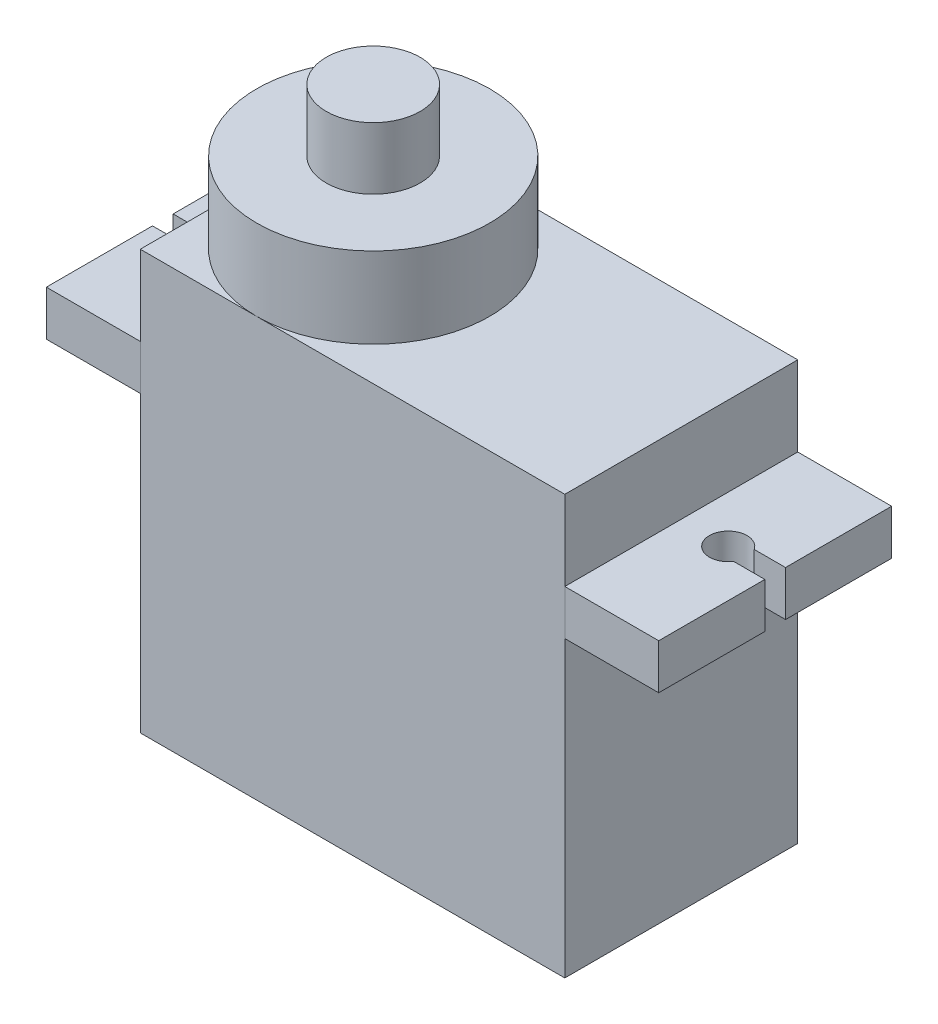
SolidWorks part; units mm, degrees
ref_plane "前视基准面" through (0, 0, 0) normal (0, 0, 1) x (1, 0, 0)
ref_plane "上视基准面" through (0, 0, 0) normal (0, 1, 0) x (1, 0, 0)
ref_plane "右视基准面" through (0, 0, 0) normal (1, 0, 0) x (0, 0, -1)
sketch "草图1" plane through (0, 0, 0) normal (0, 1, 0) x (1, 0, 0)
  line L1 (-11.3, 6.2) -> (11.3, 6.2)
  line L2 (-11.3, 6.2) -> (-11.3, -6.2)
  line L3 (-11.3, -6.2) -> (11.3, -6.2)
  line L4 (11.3, 6.2) -> (11.3, -6.2)
  line L5 (0, -6.2) -> (0, 6.2) construction
  line L6 (-11.3, 0) -> (11.3, 0) construction
  point P0 (0, 0)
  dimension "D1" = 22.6
  dimension "D2" = 12.4
extrude "凸台-拉伸1" add sketch "草图1" along normal blind 22.3
sketch "草图2" plane through (0, 0, 6.2) normal (0, 0, 1) x (1, 0, 0)
  line L0 (11.3, 22.3) -> (11.3, 0) construction
  line L1 (11.3, 18.05) -> (16.3, 18.05)
  line L2 (11.3, 18.05) -> (11.3, 15.65)
  line L3 (11.3, 15.65) -> (16.3, 15.65)
  line L4 (16.3, 18.05) -> (16.3, 15.65)
  line L5 (-11.3, 22.3) -> (11.3, 22.3) construction
  line L6 (0, 0) -> (0, 13.1092) construction
  line L7 (-11.3, 15.65) -> (-16.3, 15.65)
  line L8 (-16.3, 18.05) -> (-16.3, 15.65)
  line L9 (-11.3, 18.05) -> (-16.3, 18.05)
  line L10 (-11.3, 18.05) -> (-11.3, 15.65)
  dimension "D1" = 4.25
  dimension "D2" = 2.4
  dimension "D3" = 5
extrude "凸台-拉伸2" add sketch "草图2" against normal through all separate body
sketch "草图3" plane through (0, 18.05, 0) normal (0, 1, 0) x (1, 0, 0)
  line L0 (14.6352, 0.55) -> (16.3, 0.55)
  line L1 (16.3, 6.2) -> (16.3, -6.2) construction
  line L2 (16.3, 0.55) -> (16.3, -0.55)
  line L3 (16.3, -0.55) -> (14.6352, -0.55)
  line L4 (0, 0) -> (13.8, 0) construction
  line L5 (0, 0) -> (0, 7.8737) construction
  line L12 (-14.6352, -0.55) -> (-16.3, -0.55)
  line L13 (-16.3, 0.55) -> (-14.6352, 0.55)
  line L19 (-16.3, 0.55) -> (-16.3, -0.55)
  arc A0 (14.6352, 0.55) -> (14.6352, -0.55) centre (13.8, 0) ccw
  arc A1 (-14.6352, 0.55) -> (-14.6352, -0.55) centre (-13.8, 0) cw
  dimension "D1" = 2
  dimension "D2" = 2.5
  dimension "D3" = 1.1
extrude "切除-拉伸1" cut sketch "草图3" against normal through all
sketch "草图4" plane through (0, 22.3, 0) normal (0, 1, 0) x (1, 0, 0)
  line L1 (-11.3, 6.2) -> (-11.3, -6.2) construction
  circle A0 centre (-5.1, 0) radius 6.2
  dimension "D1" = 12.4
extrude "凸台-拉伸3" add sketch "草图4" along normal blind 4.3
sketch "草图5" plane through (0, 26.6, 0) normal (0, 1, 0) x (1, 0, 0)
  circle A0 centre (-5.1, 0) radius 2.5
  dimension "D1" = 5
extrude "凸台-拉伸4" add sketch "草图5" along normal blind 3.3
sketch "草图6" plane through (-11.3, 0, 0) normal (-1, 0, 0) x (0, 0, 1)
  line L0 (-6.2, 0) -> (6.2, 0) construction
  circle A0 centre (0, 4.5) radius 0.6
  circle A1 centre (1.2, 4.5) radius 0.6
  circle A2 centre (-1.2, 4.5) radius 0.6
  line M2 (6.2, 0) -> (6.2, 22.3)
  dimension "D1" = 1.2
  dimension "D2" = 4.5
extrude "凸台-拉伸8" add sketch "草图6" along normal blind 2.3 separate body contours A2 | A0 M2 | A1
